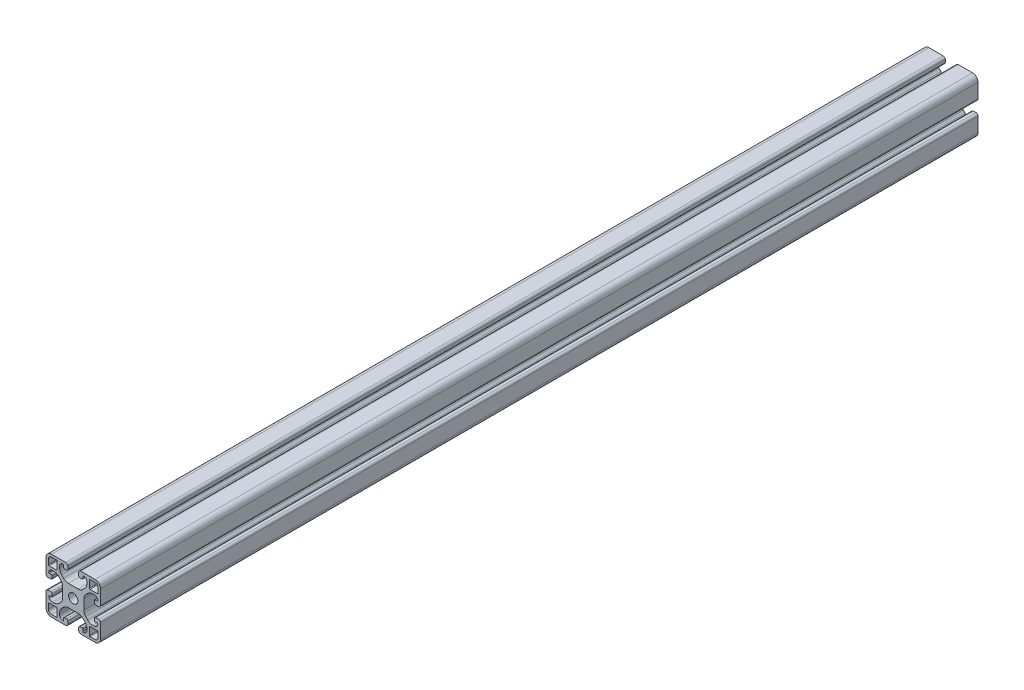
SolidWorks part; units mm, degrees
ref_plane "Plan de face" through (0, 0, 0) normal (0, 0, 1) x (1, 0, 0)
ref_plane "Plan de dessus" through (0, 0, 0) normal (0, 1, 0) x (1, 0, 0)
ref_plane "Plan de droite" through (0, 0, 0) normal (1, 0, 0) x (0, 0, -1)
ref_plane "Plan1" through (0, 0, -30) normal (0, 0, -1) x (-1, 0, 0)
sketch "Esquisse1" plane through (0, 0, -30) normal (0, 0, -1) x (-1, 0, 0)
  line L0 (-4.5, 15) -> (-4.5, 13.5)
  line L1 (-4, 13) -> (-2.5, 13)
  line L2 (-4.5, 10) -> (-5.8076, 10)
  line L3 (-9.3431, 11.4645) -> (-10.7855, 12.9069)
  line L4 (-12.25, 16.4424) -> (-12.25, 23.5576)
  line L5 (-10.7855, 27.0931) -> (-9.3431, 28.5355)
  line L6 (-5.8076, 30) -> (-4.5, 30)
  line L7 (-2.5, 27) -> (-4, 27)
  line L8 (-4.5, 26.5) -> (-4.5, 25)
  line L9 (-3.5, 24) -> (-1.5, 24)
  line L10 (0, 25.5) -> (0, 36)
  line L11 (-4, 40) -> (-14.5, 40)
  line L12 (-16, 38.5) -> (-16, 36.5)
  line L13 (-15, 35.5) -> (-13.5, 35.5)
  line L14 (-13, 36) -> (-13, 37.5)
  line L15 (-10, 35.5) -> (-10, 34.1924)
  line L16 (-11.4645, 30.6569) -> (-12.9069, 29.2145)
  line L17 (-16.4424, 27.75) -> (-23.5576, 27.75)
  line L18 (-27.0931, 29.2145) -> (-28.5355, 30.6569)
  line L19 (-30, 34.1924) -> (-30, 35.5)
  line L20 (-27, 37.5) -> (-27, 36)
  line L21 (-26.5, 35.5) -> (-25, 35.5)
  line L22 (-24, 36.5) -> (-24, 38.5)
  line L23 (-25.5, 40) -> (-36, 40)
  line L24 (-40, 36) -> (-40, 25.5)
  line L25 (-38.5, 24) -> (-36.5, 24)
  line L26 (-35.5, 25) -> (-35.5, 26.5)
  line L27 (-36, 27) -> (-37.5, 27)
  line L28 (-35.5, 30) -> (-34.1924, 30)
  line L29 (-30.6569, 28.5355) -> (-29.2145, 27.0931)
  line L30 (-27.75, 23.5576) -> (-27.75, 16.4424)
  line L31 (-29.2145, 12.9069) -> (-30.6569, 11.4645)
  line L32 (-34.1924, 10) -> (-35.5, 10)
  line L33 (-37.5, 13) -> (-36, 13)
  line L34 (-35.5, 13.5) -> (-35.5, 15)
  line L35 (-36.5, 16) -> (-38.5, 16)
  line L36 (-40, 14.5) -> (-40, 4)
  line L37 (-36, 0) -> (-25.5, 0)
  line L38 (-24, 1.5) -> (-24, 3.5)
  line L39 (-25, 4.5) -> (-26.5, 4.5)
  line L40 (-27, 4) -> (-27, 2.5)
  line L41 (-30, 4.5) -> (-30, 5.8076)
  line L42 (-28.5355, 9.3431) -> (-27.0931, 10.7855)
  line L43 (-23.5576, 12.25) -> (-16.4424, 12.25)
  line L44 (-12.9069, 10.7855) -> (-11.4645, 9.3431)
  line L45 (-10, 5.8076) -> (-10, 4.5)
  line L46 (-13, 2.5) -> (-13, 4)
  line L47 (-13.5, 4.5) -> (-15, 4.5)
  line L48 (-16, 3.5) -> (-16, 1.5)
  line L49 (-14.5, 0) -> (-4, 0)
  line L50 (0, 4) -> (0, 14.5)
  line L51 (-1.5, 16) -> (-3.5, 16)
  line L52 (-4, 1.8) -> (-7.7, 1.8)
  line L53 (-8.2, 2.3) -> (-8.2, 7.7)
  line L54 (-7.7, 8.2) -> (-2.3, 8.2)
  line L55 (-1.8, 7.7) -> (-1.8, 4)
  line L56 (-38.2, 4) -> (-38.2, 7.7)
  line L57 (-37.7, 8.2) -> (-32.3, 8.2)
  line L58 (-31.8, 7.7) -> (-31.8, 2.3)
  line L59 (-32.3, 1.8) -> (-36, 1.8)
  line L60 (-36, 38.2) -> (-32.3, 38.2)
  line L61 (-31.8, 37.7) -> (-31.8, 32.3)
  line L62 (-32.3, 31.8) -> (-37.7, 31.8)
  line L63 (-38.2, 32.3) -> (-38.2, 36)
  line L64 (-1.8, 36) -> (-1.8, 32.3)
  line L65 (-2.3, 31.8) -> (-7.7, 31.8)
  line L66 (-8.2, 32.3) -> (-8.2, 37.7)
  line L67 (-7.7, 38.2) -> (-4, 38.2)
  arc A0 (-4.5, 13.5) -> (-4, 13) centre (-4, 13.5) ccw
  arc A1 (-2.5, 13) -> (-2, 12.5) centre (-2.5, 12.5) cw
  arc A2 (-2, 12.5) -> (-4.5, 10) centre (-4.5, 12.5) cw
  arc A3 (-5.8076, 10) -> (-9.3431, 11.4645) centre (-5.8076, 15) cw
  arc A4 (-10.7855, 12.9069) -> (-12.25, 16.4424) centre (-7.25, 16.4424) cw
  arc A5 (-12.25, 23.5576) -> (-10.7855, 27.0931) centre (-7.25, 23.5576) cw
  arc A6 (-9.3431, 28.5355) -> (-5.8076, 30) centre (-5.8076, 25) cw
  arc A7 (-4.5, 30) -> (-2, 27.5) centre (-4.5, 27.5) cw
  arc A8 (-2, 27.5) -> (-2.5, 27) centre (-2.5, 27.5) cw
  arc A9 (-4, 27) -> (-4.5, 26.5) centre (-4, 26.5) ccw
  arc A10 (-4.5, 25) -> (-3.5, 24) centre (-3.5, 25) ccw
  arc A11 (-1.5, 24) -> (0, 25.5) centre (-1.5, 25.5) ccw
  arc A12 (0, 36) -> (-4, 40) centre (-4, 36) ccw
  arc A13 (-14.5, 40) -> (-16, 38.5) centre (-14.5, 38.5) ccw
  arc A14 (-16, 36.5) -> (-15, 35.5) centre (-15, 36.5) ccw
  arc A15 (-13.5, 35.5) -> (-13, 36) centre (-13.5, 36) ccw
  arc A16 (-13, 37.5) -> (-12.5, 38) centre (-12.5, 37.5) cw
  arc A17 (-12.5, 38) -> (-10, 35.5) centre (-12.5, 35.5) cw
  arc A18 (-10, 34.1924) -> (-11.4645, 30.6569) centre (-15, 34.1924) cw
  arc A19 (-12.9069, 29.2145) -> (-16.4424, 27.75) centre (-16.4424, 32.75) cw
  arc A20 (-23.5576, 27.75) -> (-27.0931, 29.2145) centre (-23.5576, 32.75) cw
  arc A21 (-28.5355, 30.6569) -> (-30, 34.1924) centre (-25, 34.1924) cw
  arc A22 (-30, 35.5) -> (-27.5, 38) centre (-27.5, 35.5) cw
  arc A23 (-27.5, 38) -> (-27, 37.5) centre (-27.5, 37.5) cw
  arc A24 (-27, 36) -> (-26.5, 35.5) centre (-26.5, 36) ccw
  arc A25 (-25, 35.5) -> (-24, 36.5) centre (-25, 36.5) ccw
  arc A26 (-24, 38.5) -> (-25.5, 40) centre (-25.5, 38.5) ccw
  arc A27 (-36, 40) -> (-40, 36) centre (-36, 36) ccw
  arc A28 (-40, 25.5) -> (-38.5, 24) centre (-38.5, 25.5) ccw
  arc A29 (-36.5, 24) -> (-35.5, 25) centre (-36.5, 25) ccw
  arc A30 (-35.5, 26.5) -> (-36, 27) centre (-36, 26.5) ccw
  arc A31 (-37.5, 27) -> (-38, 27.5) centre (-37.5, 27.5) cw
  arc A32 (-38, 27.5) -> (-35.5, 30) centre (-35.5, 27.5) cw
  arc A33 (-34.1924, 30) -> (-30.6569, 28.5355) centre (-34.1924, 25) cw
  arc A34 (-29.2145, 27.0931) -> (-27.75, 23.5576) centre (-32.75, 23.5576) cw
  arc A35 (-27.75, 16.4424) -> (-29.2145, 12.9069) centre (-32.75, 16.4424) cw
  arc A36 (-30.6569, 11.4645) -> (-34.1924, 10) centre (-34.1924, 15) cw
  arc A37 (-35.5, 10) -> (-38, 12.5) centre (-35.5, 12.5) cw
  arc A38 (-38, 12.5) -> (-37.5, 13) centre (-37.5, 12.5) cw
  arc A39 (-36, 13) -> (-35.5, 13.5) centre (-36, 13.5) ccw
  arc A40 (-35.5, 15) -> (-36.5, 16) centre (-36.5, 15) ccw
  arc A41 (-38.5, 16) -> (-40, 14.5) centre (-38.5, 14.5) ccw
  arc A42 (-40, 4) -> (-36, 0) centre (-36, 4) ccw
  arc A43 (-25.5, 0) -> (-24, 1.5) centre (-25.5, 1.5) ccw
  arc A44 (-24, 3.5) -> (-25, 4.5) centre (-25, 3.5) ccw
  arc A45 (-26.5, 4.5) -> (-27, 4) centre (-26.5, 4) ccw
  arc A46 (-27, 2.5) -> (-27.5, 2) centre (-27.5, 2.5) cw
  arc A47 (-27.5, 2) -> (-30, 4.5) centre (-27.5, 4.5) cw
  arc A48 (-30, 5.8076) -> (-28.5355, 9.3431) centre (-25, 5.8076) cw
  arc A49 (-27.0931, 10.7855) -> (-23.5576, 12.25) centre (-23.5576, 7.25) cw
  arc A50 (-16.4424, 12.25) -> (-12.9069, 10.7855) centre (-16.4424, 7.25) cw
  arc A51 (-11.4645, 9.3431) -> (-10, 5.8076) centre (-15, 5.8076) cw
  arc A52 (-10, 4.5) -> (-12.5, 2) centre (-12.5, 4.5) cw
  arc A53 (-12.5, 2) -> (-13, 2.5) centre (-12.5, 2.5) cw
  arc A54 (-13, 4) -> (-13.5, 4.5) centre (-13.5, 4) ccw
  arc A55 (-15, 4.5) -> (-16, 3.5) centre (-15, 3.5) ccw
  arc A56 (-16, 1.5) -> (-14.5, 0) centre (-14.5, 1.5) ccw
  arc A57 (-4, 0) -> (0, 4) centre (-4, 4) ccw
  arc A58 (0, 14.5) -> (-1.5, 16) centre (-1.5, 14.5) ccw
  arc A59 (-3.5, 16) -> (-4.5, 15) centre (-3.5, 15) ccw
  circle A60 centre (-20, 20) radius 3.4
  arc A61 (-1.8, 4) -> (-4, 1.8) centre (-4, 4) cw
  arc A62 (-7.7, 1.8) -> (-8.2, 2.3) centre (-7.7, 2.3) cw
  arc A63 (-8.2, 7.7) -> (-7.7, 8.2) centre (-7.7, 7.7) cw
  arc A64 (-2.3, 8.2) -> (-1.8, 7.7) centre (-2.3, 7.7) cw
  arc A65 (-36, 1.8) -> (-38.2, 4) centre (-36, 4) cw
  arc A66 (-38.2, 7.7) -> (-37.7, 8.2) centre (-37.7, 7.7) cw
  arc A67 (-32.3, 8.2) -> (-31.8, 7.7) centre (-32.3, 7.7) cw
  arc A68 (-31.8, 2.3) -> (-32.3, 1.8) centre (-32.3, 2.3) cw
  arc A69 (-38.2, 36) -> (-36, 38.2) centre (-36, 36) cw
  arc A70 (-32.3, 38.2) -> (-31.8, 37.7) centre (-32.3, 37.7) cw
  arc A71 (-31.8, 32.3) -> (-32.3, 31.8) centre (-32.3, 32.3) cw
  arc A72 (-37.7, 31.8) -> (-38.2, 32.3) centre (-37.7, 32.3) cw
  arc A73 (-4, 38.2) -> (-1.8, 36) centre (-4, 36) cw
  arc A74 (-1.8, 32.3) -> (-2.3, 31.8) centre (-2.3, 32.3) cw
  arc A75 (-7.7, 31.8) -> (-8.2, 32.3) centre (-7.7, 32.3) cw
  arc A76 (-8.2, 37.7) -> (-7.7, 38.2) centre (-7.7, 37.7) cw
extrude "Boss.-Extru.1" add sketch "Esquisse1" against normal blind 644
